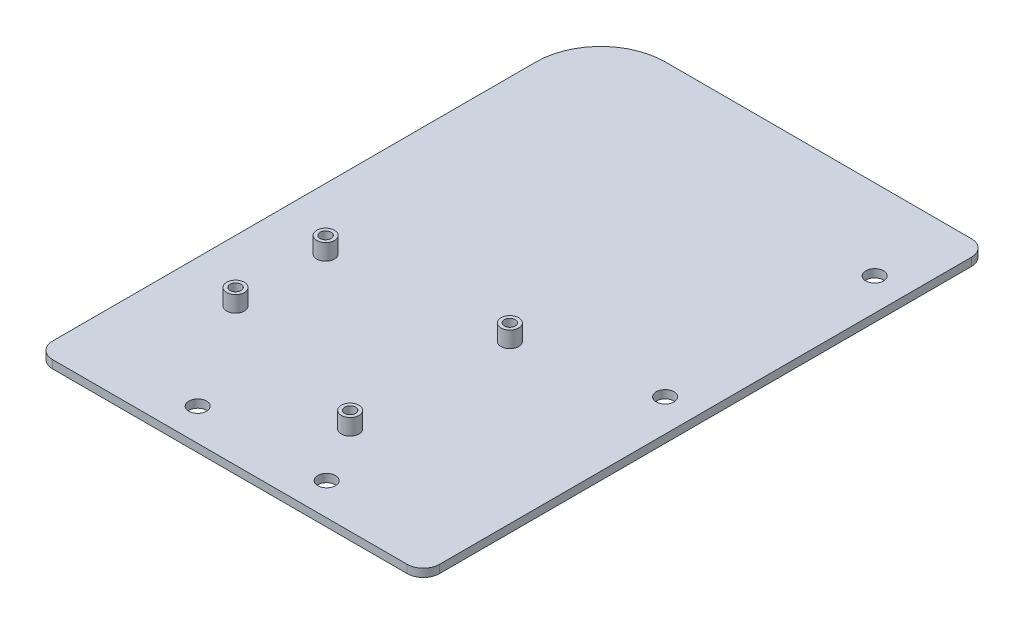
SolidWorks part; units mm, degrees
ref_plane "Front Plane" through (0, 0, 0) normal (0, 0, 1) x (1, 0, 0)
ref_plane "Top Plane" through (0, 0, 0) normal (0, 1, 0) x (1, 0, 0)
ref_plane "Right Plane" through (0, 0, 0) normal (1, 0, 0) x (0, 0, -1)
sketch "Sketch1" plane through (0, 0, 0) normal (0, 1, 0) x (1, 0, 0)
  line L1 (-60, -87.5) -> (60, -87.5)
  line L2 (-60, -87.5) -> (-60, 87.5)
  line L3 (-60, 87.5) -> (60, 87.5)
  line L4 (60, -87.5) -> (60, 87.5)
  line L5 (-60, -87.5) -> (60, 87.5) construction
  line L6 (-60, 87.5) -> (60, -87.5) construction
  point P0 (0, 0)
  dimension "D1" = 175
  dimension "D2" = 120
extrude "Boss-Extrude1" add sketch "Sketch1" along normal blind 2.5
sketch "Sketch2" plane through (0, 2.5, 0) normal (0, 1, 0) x (1, 0, 0)
  line L0 (40, 87.5) -> (40, -87.5) construction
  line L1 (60, 87.5) -> (-60, 87.5) construction
  line L2 (-60, -87.5) -> (60, -87.5) construction
  line L3 (-60, -67.5) -> (60, -67.5) construction
  line L4 (-60, 87.5) -> (-60, -87.5) construction
  line L5 (60, -87.5) -> (60, 87.5) construction
  dimension "D1" = 20
  dimension "D2" = 20
hole_wizard "M5 Clearance Hole1" positions "Sketch3" profile "Sketch4" hole size "M5" standard "ANSI Metric" end condition through all
sketch "Sketch3" plane through (0, 2.5, 0) normal (0, 1, 0) x (1, 0, 0)
  line L0 (50, 62.5) -> (50, -2.5) construction
  line L2 (-20, -77.5) -> (20, -77.5) construction
  line L4 (60, -87.5) -> (60, 87.5) construction
  line L5 (-60, -87.5) -> (60, -87.5) construction
  line L6 (-60, -67.5) -> (60, -67.5) construction
  line L7 (40, 87.5) -> (40, -87.5) construction
  line L8 (60, 87.5) -> (-60, 87.5) construction
  point P0 (50, 62.5)
  point P2 (50, -2.5)
  point P4 (-20, -77.5)
  point P7 (20, -77.5)
  dimension "D1" = 10
  dimension "D2" = 10
  dimension "D3" = 65
  dimension "D4" = 25
  dimension "D5" = 20
  dimension "D6" = 40
sketch "Sketch4" plane through (50, 2.5, -62.5) normal (1, 0, 0) x (0, 0, 1)
  line L0 (0, 0) -> (0, 2.5)
  line L1 (0, 2.5) -> (2.75, 2.5)
  line L2 (2.75, 2.5) -> (2.75, 0)
  line L5 (2.75, 0) -> (0, 0)
  line L11 (0, -6.35) -> (0, 107.95) construction
  dimension "Thru Hole Dia." = 5.5
  dimension "Thru Hole Depth" = 2.5
sketch "Sketch5" plane through (0, 2.5, 0) normal (0, 1, 0) x (1, 0, 0)
  line L1 (-45, 83.7021) -> (7, 83.7021)
  line L2 (-45, 83.7021) -> (-45, 3.7021)
  line L3 (-45, 3.7021) -> (7, 3.7021)
  line L4 (7, 83.7021) -> (7, 3.7021)
  line L5 (-45, -2.5) -> (25, -2.5)
  line L6 (-45, -2.5) -> (-45, -62.5)
  line L7 (-45, -62.5) -> (25, -62.5)
  line L8 (25, -2.5) -> (25, -62.5)
  line L9 (-60, 87.5) -> (-60, -87.5) construction
  line L10 (-60, -87.5) -> (60, -87.5) construction
  dimension "D1" = 80
  dimension "D2" = 52
  dimension "D3" = 60
  dimension "D4" = 70
  dimension "D5" = 25
  dimension "D6" = 15
  dimension "D8" = 15
hole_wizard "M3 Clearance Hole2" positions "Sketch9" profile "Sketch10" hole size "M3" standard "ANSI Metric" end condition through all
sketch "Sketch9" plane through (0, 2.5, 0) normal (0, 1, 0) x (1, 0, 0)
  line L0 (-45, -62.5) -> (25, -62.5) construction
  line L1 (25, -2.5) -> (25, -62.5) construction
  point P0 (9.76, -59.96)
  point P2 (11.03, -11.7)
  point P4 (-41.04, -44.72)
  point P6 (-41.04, -16.78)
  dimension "D1" = 2.54
  dimension "D2" = 15.24
  dimension "D3" = 13.97
  dimension "D4" = 50.8
  dimension "D5" = 66.04
  dimension "D6" = 17.78
  dimension "D7" = 45.72
sketch "Sketch10" plane through (9.76, 2.5, 59.96) normal (1, 0, 0) x (0, 0, 1)
  line L0 (0, 0) -> (0, 2.5)
  line L1 (0, 2.5) -> (1.7, 2.5)
  line L2 (1.7, 2.5) -> (1.7, 0)
  line L5 (1.7, 0) -> (0, 0)
  line L11 (0, -6.35) -> (0, 107.95) construction
  dimension "Thru Hole Dia." = 3.4
  dimension "Thru Hole Depth" = 2.5
fillet "Fillet1" radius 20 1 edges at (-60, 1.25, -87.5)
fillet "Fillet2" radius 5 3 edges at (-60, 1.25, 87.5) (60, 1.25, 87.5) (60, 1.25, -87.5)
sketch "Sketch11" plane through (0, 2.5, 0) normal (0, 1, 0) x (1, 0, 0)
  circle A0 centre (-41.04, -16.78) radius 1.7
  circle A1 centre (-41.04, -16.78) radius 2.75
  circle A2 centre (-41.04, -16.78) radius 1.7 construction
  dimension "D1" = 5.5
extrude "Boss-Extrude3" add sketch "Sketch11" along normal blind 5
pattern_sketch "Sketch-Pattern2" of "Boss-Extrude3" driven by "Sketch9"
